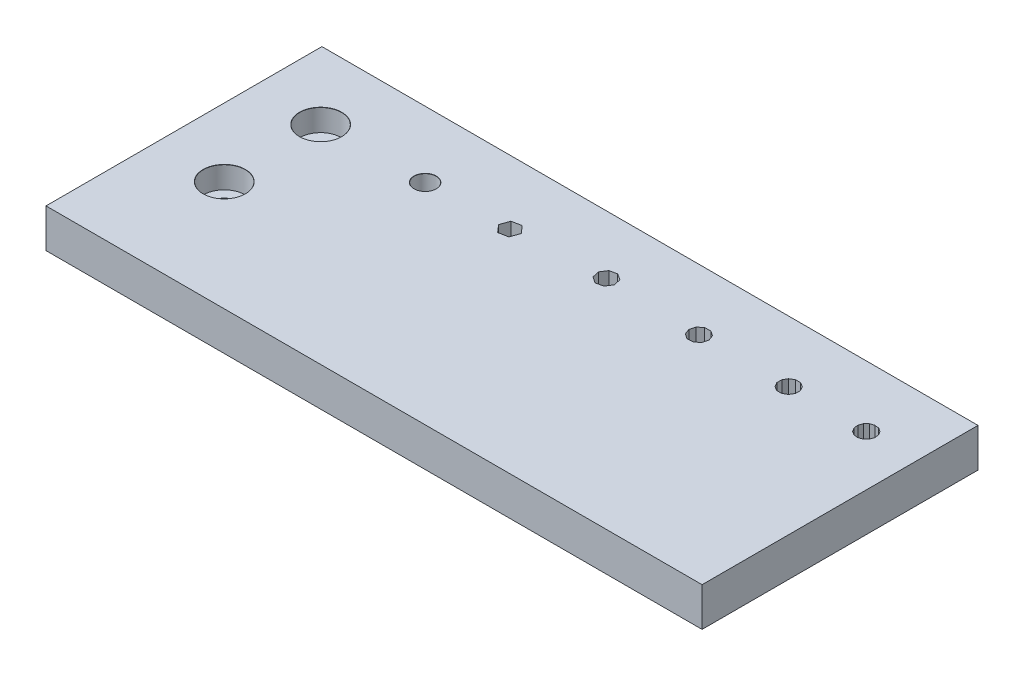
SolidWorks part; units mm, degrees
ref_plane "Front Plane" through (0, 0, 0) normal (0, 0, 1) x (1, 0, 0)
ref_plane "Top Plane" through (0, 0, 0) normal (0, 1, 0) x (1, 0, 0)
ref_plane "Right Plane" through (0, 0, 0) normal (1, 0, 0) x (0, 0, -1)
sketch "Sketch1" plane through (0, 0, 0) normal (0, 1, 0) x (1, 0, 0)
  line L0 (-38.6508, 19.3444) -> (-38.5038, 20.1069)
  line L5 (-38.5038, 20.1069) -> (-38.7577, 20.8406)
  line L6 (-38.7577, 20.8406) -> (-39.3444, 21.3492)
  line L7 (-38.6508, 39.3444) -> (-38.5038, 40.1069)
  line L8 (-38.5038, 40.1069) -> (-38.7577, 40.8406)
  line L9 (-38.7577, 40.8406) -> (-39.3444, 41.3492)
  line L10 (-39.3444, 41.3492) -> (-40.1069, 41.4962)
  line L11 (-40.1069, 41.4962) -> (-40.8406, 41.2423)
  line L12 (-40.8406, 41.2423) -> (-41.3492, 40.6556)
  line L13 (-41.3492, 40.6556) -> (-41.4962, 39.8931)
  line L14 (-41.4962, 39.8931) -> (-41.2423, 39.1594)
  line L15 (-41.2423, 39.1594) -> (-40.6556, 38.6508)
  line L16 (-40.6556, 38.6508) -> (-39.8931, 38.5038)
  line L17 (-39.8931, 38.5038) -> (-39.1594, 38.7577)
  line L18 (-39.1594, 38.7577) -> (-38.6508, 39.3444)
  line L19 (-18.6508, 39.3444) -> (-18.5232, 40.2627)
  line L20 (-18.5232, 40.2627) -> (-18.9596, 41.0806)
  line L21 (-18.9596, 41.0806) -> (-19.7934, 41.4857)
  line L22 (-19.7934, 41.4857) -> (-20.7062, 41.3234)
  line L23 (-20.7062, 41.3234) -> (-21.3492, 40.6556)
  line L24 (-21.3492, 40.6556) -> (-21.4768, 39.7373)
  line L25 (-21.4768, 39.7373) -> (-21.0404, 38.9194)
  line L26 (-21.0404, 38.9194) -> (-20.2066, 38.5143)
  line L27 (-20.2066, 38.5143) -> (-19.2938, 38.6766)
  line L28 (-19.2938, 38.6766) -> (-18.6508, 39.3444)
  line L29 (1.0404, 38.9194) -> (1.4997, 39.9716)
  line L30 (1.4997, 39.9716) -> (1.0806, 41.0404)
  line L31 (1.0806, 41.0404) -> (0.0284, 41.4997)
  line L32 (0.0284, 41.4997) -> (-1.0404, 41.0806)
  line L33 (-1.0404, 41.0806) -> (-1.4997, 40.0284)
  line L34 (-1.4997, 40.0284) -> (-1.0806, 38.9596)
  line L35 (-1.0806, 38.9596) -> (-0.0284, 38.5003)
  line L36 (-0.0284, 38.5003) -> (1.0404, 38.9194)
  line L37 (21.4768, 39.7373) -> (20.9659, 41.1476)
  line L38 (20.9659, 41.1476) -> (19.4891, 41.4103)
  line L39 (19.4891, 41.4103) -> (18.5232, 40.2627)
  line L40 (18.5232, 40.2627) -> (19.0341, 38.8524)
  line L41 (19.0341, 38.8524) -> (20.5109, 38.5897)
  line L42 (20.5109, 38.5897) -> (21.4768, 39.7373)
  line L43 (41.3914, 39.4395) -> (40.5605, 41.3914)
  line L44 (40.5605, 41.3914) -> (38.6086, 40.5605)
  line L45 (38.6086, 40.5605) -> (39.4395, 38.6086)
  line L46 (39.4395, 38.6086) -> (41.3914, 39.4395)
  line L47 (-39.3444, 21.3492) -> (-40.1069, 21.4962)
  line L48 (-40.1069, 21.4962) -> (-40.8406, 21.2423)
  line L49 (-40.8406, 21.2423) -> (-41.3492, 20.6556)
  line L50 (-41.3492, 20.6556) -> (-41.4962, 19.8931)
  line L51 (-41.4962, 19.8931) -> (-41.2423, 19.1594)
  line L52 (-41.2423, 19.1594) -> (-40.6556, 18.6508)
  line L53 (-40.6556, 18.6508) -> (-39.8931, 18.5038)
  line L54 (-39.8931, 18.5038) -> (-39.1594, 18.7577)
  line L55 (-39.1594, 18.7577) -> (-38.6508, 19.3444)
  line L56 (-18.6508, 19.3444) -> (-18.5232, 20.2627)
  line L57 (-18.5232, 20.2627) -> (-18.9596, 21.0806)
  line L58 (-18.9596, 21.0806) -> (-19.7934, 21.4857)
  line L59 (-19.7934, 21.4857) -> (-20.7062, 21.3234)
  line L60 (-20.7062, 21.3234) -> (-21.3492, 20.6556)
  line L61 (-21.3492, 20.6556) -> (-21.4768, 19.7373)
  line L62 (-21.4768, 19.7373) -> (-21.0404, 18.9194)
  line L63 (-21.0404, 18.9194) -> (-20.2066, 18.5143)
  line L64 (-20.2066, 18.5143) -> (-19.2938, 18.6766)
  line L65 (-19.2938, 18.6766) -> (-18.6508, 19.3444)
  line L66 (1.0404, 18.9194) -> (1.4997, 19.9716)
  line L67 (1.4997, 19.9716) -> (1.0806, 21.0404)
  line L68 (1.0806, 21.0404) -> (0.0284, 21.4997)
  line L69 (0.0284, 21.4997) -> (-1.0404, 21.0806)
  line L70 (-1.0404, 21.0806) -> (-1.4997, 20.0284)
  line L71 (-1.4997, 20.0284) -> (-1.0806, 18.9596)
  line L72 (-1.0806, 18.9596) -> (-0.0284, 18.5003)
  line L73 (-0.0284, 18.5003) -> (1.0404, 18.9194)
  line L74 (21.4768, 19.7373) -> (20.9659, 21.1476)
  line L75 (20.9659, 21.1476) -> (19.4891, 21.4103)
  line L76 (19.4891, 21.4103) -> (18.5232, 20.2627)
  line L77 (18.5232, 20.2627) -> (19.0341, 18.8524)
  line L78 (19.0341, 18.8524) -> (20.5109, 18.5897)
  line L79 (20.5109, 18.5897) -> (21.4768, 19.7373)
  line L80 (41.3914, 19.4395) -> (40.5605, 21.3914)
  line L81 (40.5605, 21.3914) -> (38.6086, 20.5605)
  line L82 (38.6086, 20.5605) -> (39.4395, 18.6086)
  line L83 (39.4395, 18.6086) -> (41.3914, 19.4395)
  line L85 (41.2145, -3.2425) -> (-60.3855, -3.2425)
  line L86 (41.2145, -3.2425) -> (41.2145, -45.9701)
  line L87 (41.2145, -45.9701) -> (-60.3855, -45.9701)
  line L88 (-60.3855, -3.2425) -> (-60.3855, -45.9701)
  circle A41 centre (-40, 40) radius 1.4489 construction
  circle A43 centre (-20, 40) radius 1.4266 construction
  circle A45 centre (0, 40) radius 1.3858 construction
  circle A47 centre (20, 40) radius 1.299 construction
  circle A49 centre (40, 40) radius 1.0607 construction
  circle A50 centre (-40, 20) radius 1.4489 construction
  circle A51 centre (-20, 20) radius 1.4266 construction
  circle A52 centre (0, 20) radius 1.3858 construction
  circle A53 centre (20, 20) radius 1.299 construction
  circle A54 centre (40, 20) radius 1.0607 construction
extrude "Boss-Extrude2" add sketch "Sketch1" along normal blind 6 contours L86 L85 L88 L87
sketch "Sketch3" plane through (0, 6, 0) normal (0, 1, 0) x (1, 0, 0)
sketch "Sketch6" plane through (0, 6, 0) normal (0, 1, 0) x (1, 0, 0)
  point P0 (-50.0443, -13.7823)
  point P2 (-50.0443, -13.7823)
hole_wizard "CBORE for M3 Hex Socket Head Cap Screw1" positions "Sketch6" profile "Sketch5" counterbore size "M3" standard "ISO" end condition through all
sketch "Sketch5" plane through (-50.0443, 6, 13.7823) normal (1, 0, 0) x (0, 0, 1)
  line L0 (0, 0) -> (0, 6)
  line L1 (0, 6) -> (1.6, 6)
  line L3 (1.6, 6) -> (1.6, 3.4)
  line L4 (3.25, 3.4) -> (1.6, 3.4)
  line L5 (3.25, 3.4) -> (3.25, 0.025)
  line L6 (3.25, 0.025) -> (3.275, 0)
  line L7 (3.275, 0) -> (0, 0)
  line L8 (-3.25, 0.025) -> (-3.275, 0) construction
  line L11 (0, -6.35) -> (0, 107.95) construction
  dimension "Thru Hole Dia." = 3.2
  dimension "Thru Hole Depth" = 6
  dimension "C'Bore Dia." = 6.5
  dimension "C'Bore Depth" = 3.4
  dimension "Near C'Sink Dia." = 6.55
  dimension "Near C'Sink Angle" = 90
sketch "Sketch9" plane through (0, 6, 0) normal (0, 1, 0) x (1, 0, 0)
  point P0 (-49.8341, -28.9149)
hole_wizard "CBORE for M3 Hex Socket Head Cap Screw2" positions "Sketch9" profile "Sketch8" counterbore size "M3" standard "ISO" end condition through all
sketch "Sketch8" plane through (-49.8341, 6, 28.9149) normal (1, 0, 0) x (0, 0, 1)
  line L0 (0, 0) -> (0, 6)
  line L1 (0, 6) -> (1.7, 6)
  line L3 (1.7, 6) -> (1.7, 3.4)
  line L4 (3.25, 3.4) -> (1.7, 3.4)
  line L5 (3.25, 3.4) -> (3.25, 0.025)
  line L6 (3.25, 0.025) -> (3.275, 0)
  line L7 (3.275, 0) -> (0, 0)
  line L8 (-3.25, 0.025) -> (-3.275, 0) construction
  line L11 (0, -6.35) -> (0, 107.95) construction
  dimension "Thru Hole Dia." = 3.4
  dimension "Thru Hole Depth" = 6
  dimension "C'Bore Dia." = 6.5
  dimension "C'Bore Depth" = 3.4
  dimension "Near C'Sink Dia." = 6.55
  dimension "Near C'Sink Angle" = 90
sketch "Sketch12" plane through (0, 6, 0) normal (0, 1, 0) x (1, 0, 0)
  point P0 (-32.2845, -13.3619)
sketch "Sketch16" plane through (0, 6, 0) normal (0, 1, 0) x (1, 0, 0)
  point P0 (-34.176, -13.467)
hole_wizard "M3 Clearance Hole1" positions "Sketch16" profile "Sketch15" hole size "M3" standard "ISO" end condition through all
sketch "Sketch15" plane through (-34.176, 6, 13.467) normal (1, 0, 0) x (0, 0, 1)
  line L0 (0, 0) -> (0, 6)
  line L1 (0, 6) -> (1.7, 6)
  line L2 (1.7, 6) -> (1.7, 0.025)
  line L3 (1.7, 0.025) -> (1.725, 0)
  line L5 (1.725, 0) -> (0, 0)
  line L6 (-1.7, 0.025) -> (-1.725, 0) construction
  line L11 (0, -6.35) -> (0, 107.95) construction
  dimension "Thru Hole Dia." = 3.4
  dimension "Thru Hole Depth" = 6
  dimension "Near C'Sink Dia." = 3.45
  dimension "Near C'Sink Angle" = 90
sketch "Sketch17" plane through (0, 6, 0) normal (0, 1, 0) x (1, 0, 0)
  line L1 (-20.3742, -14.2913) -> (-19.8822, -12.8743)
  line L2 (-19.8822, -12.8743) -> (-20.8633, -11.7397)
  line L3 (-20.8633, -11.7397) -> (-22.3365, -12.0221)
  line L4 (-22.3365, -12.0221) -> (-22.8285, -13.4391)
  line L5 (-22.8285, -13.4391) -> (-21.8473, -14.5737)
  line L6 (-21.8473, -14.5737) -> (-20.3742, -14.2913)
  circle A1 centre (-21.3553, -13.1567) radius 1.299 construction
extrude "Cut-Extrude1" cut sketch "Sketch17" against normal through all contours L5 L6 L1 L2 L3 L4
sketch "Sketch18" plane through (0, 6, 0) normal (0, 1, 0) x (1, 0, 0)
  line L1 (-6.4268, -13.5352) -> (-5.7993, -12.5738)
  line L2 (-5.7993, -12.5738) -> (-6.0355, -11.4503)
  line L3 (-6.0355, -11.4503) -> (-6.9969, -10.8228)
  line L4 (-6.9969, -10.8228) -> (-8.1204, -11.059)
  line L5 (-8.1204, -11.059) -> (-8.7478, -12.0204)
  line L6 (-8.7478, -12.0204) -> (-8.5117, -13.1439)
  line L7 (-8.5117, -13.1439) -> (-7.5503, -13.7714)
  line L8 (-7.5503, -13.7714) -> (-6.4268, -13.5352)
  line L9 (8.7046, -13.5352) -> (8.9557, -12.6428)
  line L10 (8.9557, -12.6428) -> (8.6343, -11.7733)
  line L11 (8.6343, -11.7733) -> (7.8632, -11.2587)
  line L12 (7.8632, -11.2587) -> (6.9369, -11.2956)
  line L13 (6.9369, -11.2956) -> (6.2092, -11.8699)
  line L14 (6.2092, -11.8699) -> (5.9581, -12.7623)
  line L15 (5.9581, -12.7623) -> (6.2795, -13.6319)
  line L16 (6.2795, -13.6319) -> (7.0506, -14.1465)
  line L17 (7.0506, -14.1465) -> (7.9769, -14.1096)
  line L18 (7.9769, -14.1096) -> (8.7046, -13.5352)
  line L19 (22.4019, -13.7714) -> (22.7953, -13.1019)
  line L20 (22.7953, -13.1019) -> (22.8012, -12.3255)
  line L21 (22.8012, -12.3255) -> (22.4182, -11.6501)
  line L22 (22.4182, -11.6501) -> (21.7488, -11.2567)
  line L23 (21.7488, -11.2567) -> (20.9723, -11.2507)
  line L24 (20.9723, -11.2507) -> (20.2969, -11.6338)
  line L25 (20.2969, -11.6338) -> (19.9035, -12.3032)
  line L26 (19.9035, -12.3032) -> (19.8976, -13.0796)
  line L27 (19.8976, -13.0796) -> (20.2806, -13.755)
  line L28 (20.2806, -13.755) -> (20.95, -14.1484)
  line L29 (20.95, -14.1484) -> (21.7265, -14.1544)
  line L30 (21.7265, -14.1544) -> (22.4019, -13.7714)
  line L31 (34.169, -13.9771) -> (34.6436, -13.5077)
  line L32 (34.6436, -13.5077) -> (34.8676, -12.8788)
  line L33 (34.8676, -12.8788) -> (34.7965, -12.215)
  line L34 (34.7965, -12.215) -> (34.4445, -11.6478)
  line L35 (34.4445, -11.6478) -> (33.8812, -11.2895)
  line L36 (33.8812, -11.2895) -> (33.2183, -11.2111)
  line L37 (33.2183, -11.2111) -> (32.587, -11.4281)
  line L38 (32.587, -11.4281) -> (32.1123, -11.8975)
  line L39 (32.1123, -11.8975) -> (31.8884, -12.5264)
  line L40 (31.8884, -12.5264) -> (31.9594, -13.1901)
  line L41 (31.9594, -13.1901) -> (32.3115, -13.7573)
  line L42 (32.3115, -13.7573) -> (32.8747, -14.1156)
  line L43 (32.8747, -14.1156) -> (33.5377, -14.1941)
  line L44 (33.5377, -14.1941) -> (34.169, -13.9771)
  circle A4 centre (-7.2736, -12.2971) radius 1.3858 construction
  circle A5 centre (7.4569, -12.7026) radius 1.4266 construction
  circle A6 centre (21.3494, -12.7026) radius 1.4489 construction
  circle A7 centre (33.378, -12.7026) radius 1.4624 construction
extrude "Cut-Extrude2" cut sketch "Sketch18" against normal through all
